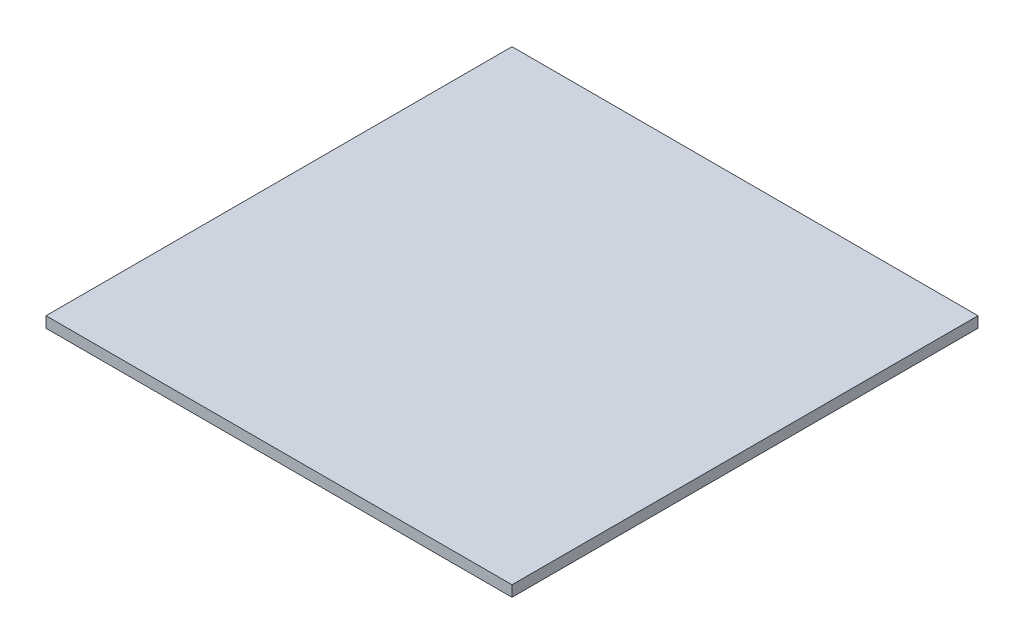
SolidWorks part; units mm, degrees
ref_plane "Front Plane" through (0, 0, 0) normal (0, 0, 1) x (1, 0, 0)
ref_plane "Top Plane" through (0, 0, 0) normal (0, 1, 0) x (1, 0, 0)
ref_plane "Right Plane" through (0, 0, 0) normal (1, 0, 0) x (0, 0, -1)
sketch "Sketch1" plane through (0, 0, 0) normal (0, 1, 0) x (1, 0, 0)
  line L1 (-107, -107) -> (107, -107)
  line L2 (-107, -107) -> (-107, 107)
  line L3 (-107, 107) -> (107, 107)
  line L4 (107, -107) -> (107, 107)
  line L5 (-107, -107) -> (107, 107) construction
  line L6 (-107, 107) -> (107, -107) construction
  point P0 (0, 0)
  dimension "D1" = 214
  dimension "D2" = 214
extrude "Boss-Extrude1" add sketch "Sketch1" along normal blind 5
